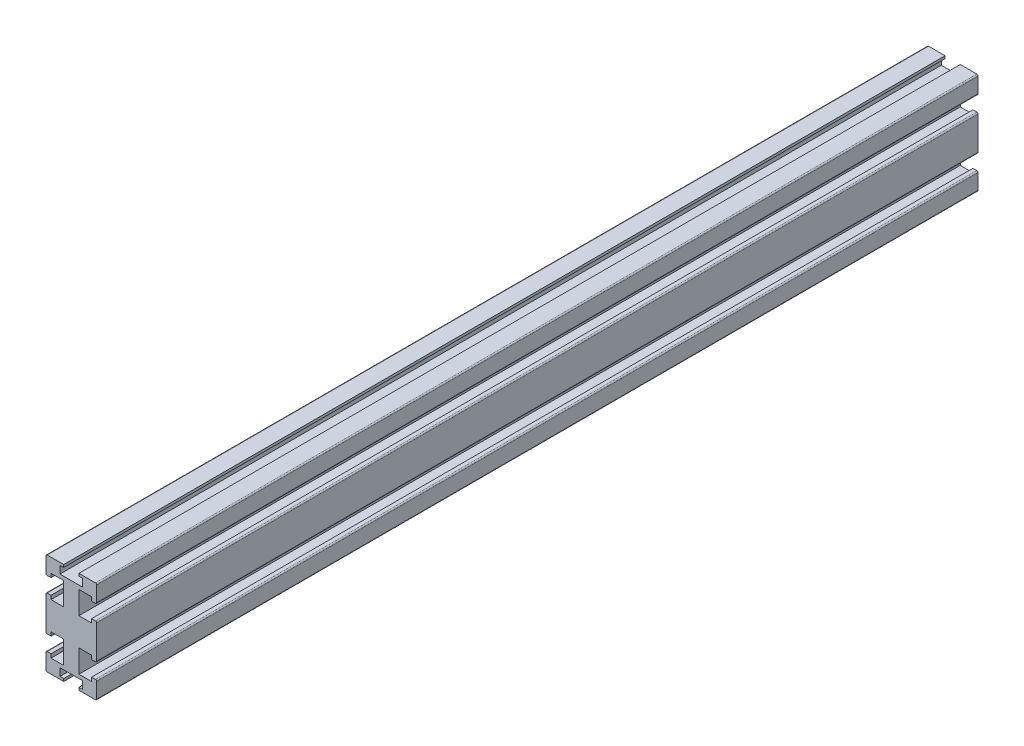
SolidWorks part; units mm, degrees
ref_plane "前基準面" through (0, 0, 0) normal (0, 0, 1) x (1, 0, 0)
ref_plane "上基準面" through (0, 0, 0) normal (0, 1, 0) x (1, 0, 0)
ref_plane "右基準面" through (0, 0, 0) normal (1, 0, 0) x (0, 0, -1)
sketch "草圖1" plane through (0, 0, 0) normal (0, 0, 1) x (1, 0, 0)
  line L0 (0, 0) -> (0, 52.5376) construction
  line L1 (0, 0) -> (28.5856, 0) construction
  line L2 (-4.5, 4) -> (4.5, 4)
  line L3 (4.5, 4) -> (4.5, 1)
  line L4 (4.5, 1) -> (3, 1)
  line L5 (3, 1) -> (3, 0)
  line L6 (3, 0) -> (10, 0)
  line L7 (10, 0) -> (10, 7)
  line L8 (10, 7) -> (8, 7)
  line L9 (8, 7) -> (8, 5.5)
  line L10 (8, 5.5) -> (3, 5.5)
  line L11 (3, 5.5) -> (3, 14.5)
  line L12 (3, 14.5) -> (8, 14.5)
  line L13 (8, 14.5) -> (8, 13)
  line L14 (8, 13) -> (10, 13)
  line L15 (10, 13) -> (10, 27)
  line L16 (10, 20) -> (-10, 20) construction
  line L17 (3, 10) -> (8, 10) construction
  line L18 (3, 30) -> (8, 30) construction
  line L19 (8, 27) -> (10, 27)
  line L20 (8, 25.5) -> (8, 27)
  line L21 (3, 25.5) -> (8, 25.5)
  line L22 (3, 34.5) -> (3, 25.5)
  line L23 (8, 34.5) -> (3, 34.5)
  line L24 (8, 33) -> (8, 34.5)
  line L25 (10, 33) -> (8, 33)
  line L26 (10, 40) -> (10, 33)
  line L27 (3, 40) -> (10, 40)
  line L28 (3, 39) -> (3, 40)
  line L29 (4.5, 39) -> (3, 39)
  line L30 (4.5, 36) -> (4.5, 39)
  line L31 (-4.5, 36) -> (4.5, 36)
  line L32 (-3, 30) -> (-8, 30) construction
  line L33 (-3, 10) -> (-8, 10) construction
  line L34 (-4.5, 36) -> (-4.5, 39)
  line L35 (-4.5, 39) -> (-3, 39)
  line L36 (-3, 39) -> (-3, 40)
  line L37 (-3, 40) -> (-10, 40)
  line L38 (-10, 40) -> (-10, 33)
  line L39 (-10, 33) -> (-8, 33)
  line L40 (-8, 33) -> (-8, 34.5)
  line L41 (-8, 34.5) -> (-3, 34.5)
  line L42 (-3, 34.5) -> (-3, 25.5)
  line L43 (-3, 25.5) -> (-8, 25.5)
  line L44 (-8, 25.5) -> (-8, 27)
  line L45 (-8, 27) -> (-10, 27)
  line L46 (-10, 13) -> (-10, 27)
  line L47 (-8, 13) -> (-10, 13)
  line L48 (-8, 14.5) -> (-8, 13)
  line L49 (-3, 14.5) -> (-8, 14.5)
  line L50 (-3, 5.5) -> (-3, 14.5)
  line L51 (-8, 5.5) -> (-3, 5.5)
  line L52 (-8, 7) -> (-8, 5.5)
  line L53 (-10, 7) -> (-8, 7)
  line L54 (-10, 0) -> (-10, 7)
  line L55 (-3, 0) -> (-10, 0)
  line L56 (-3, 1) -> (-3, 0)
  line L57 (-4.5, 1) -> (-3, 1)
  line L58 (-4.5, 4) -> (-4.5, 1)
  point P43 (0, 20)
  point P44 (0, 36)
  point P69 (0, 4)
  dimension "D1" = 20
  dimension "D2" = 1
  dimension "D3" = 5
  dimension "D4" = 7
  dimension "D5" = 9
  dimension "D6" = 6
  dimension "D7" = 6
  dimension "D8" = 9
  dimension "D9" = 20
  dimension "D10" = 3
  dimension "D11" = 10
extrude "填料-伸長1" add sketch "草圖1" along normal blind 348
fillet "圓角1" radius 0.5 12 edges at (10, 33, 174) (-10, 0, 174) (-10, 7, 174) (-10, 13, 174) (-10, 27, 174) (-10, 33, 174) (10, 0, 174) (10, 7, 174) (10, 13, 174) (10, 27, 174) (10, 40, 174) (-10, 40, 174)
